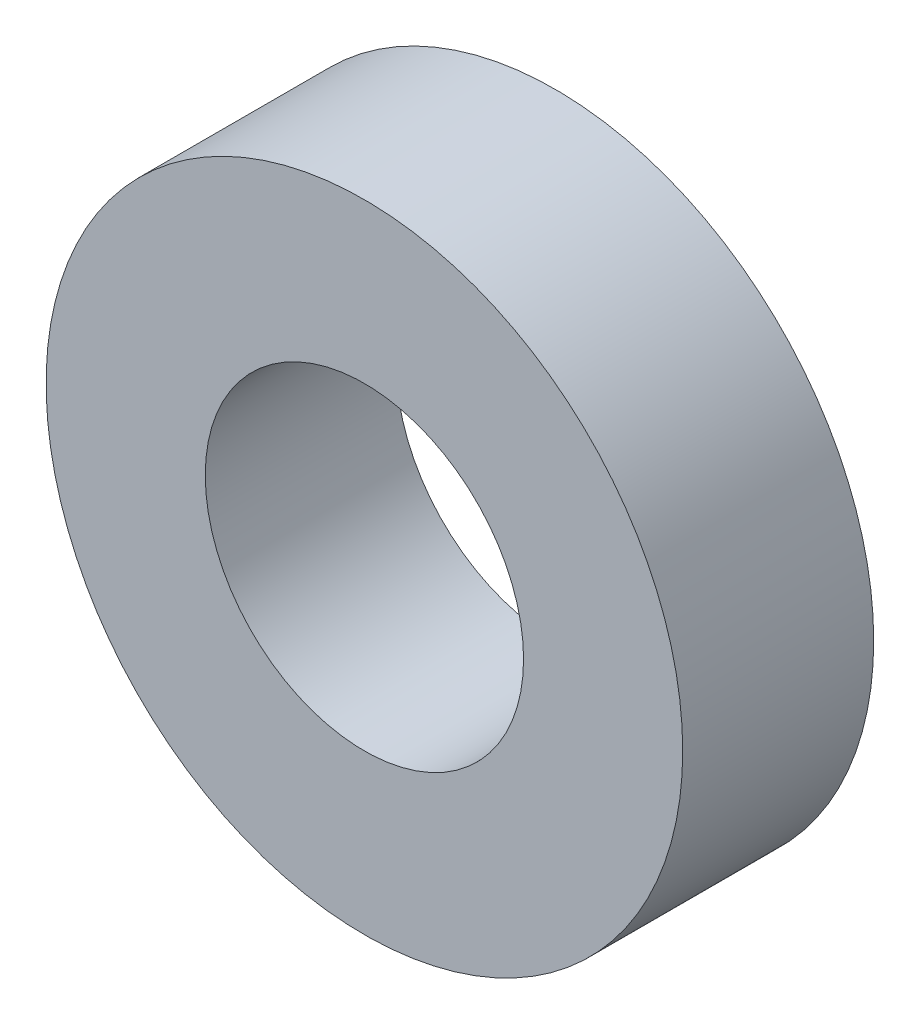
SolidWorks part; units mm, degrees
ref_plane "Alzado" through (0, 0, 0) normal (0, 0, 1) x (1, 0, 0)
ref_plane "Planta" through (0, 0, 0) normal (0, 1, 0) x (1, 0, 0)
ref_plane "Vista lateral" through (0, 0, 0) normal (1, 0, 0) x (0, 0, -1)
sketch "Croquis1" plane through (0, 0, 0) normal (0, 0, 1) x (1, 0, 0)
  circle A0 centre (0, 0) radius 5
  dimension "D1" = 10
extrude "Saliente-Extruir1" add sketch "Croquis1" along normal blind 3
sketch "Croquis2" plane through (0, 0, 3) normal (0, 0, 1) x (1, 0, 0)
  circle A0 centre (0, 0) radius 2.5
  dimension "D1" = 5
extrude "Cortar-Extruir1" cut sketch "Croquis2" against normal up to next
